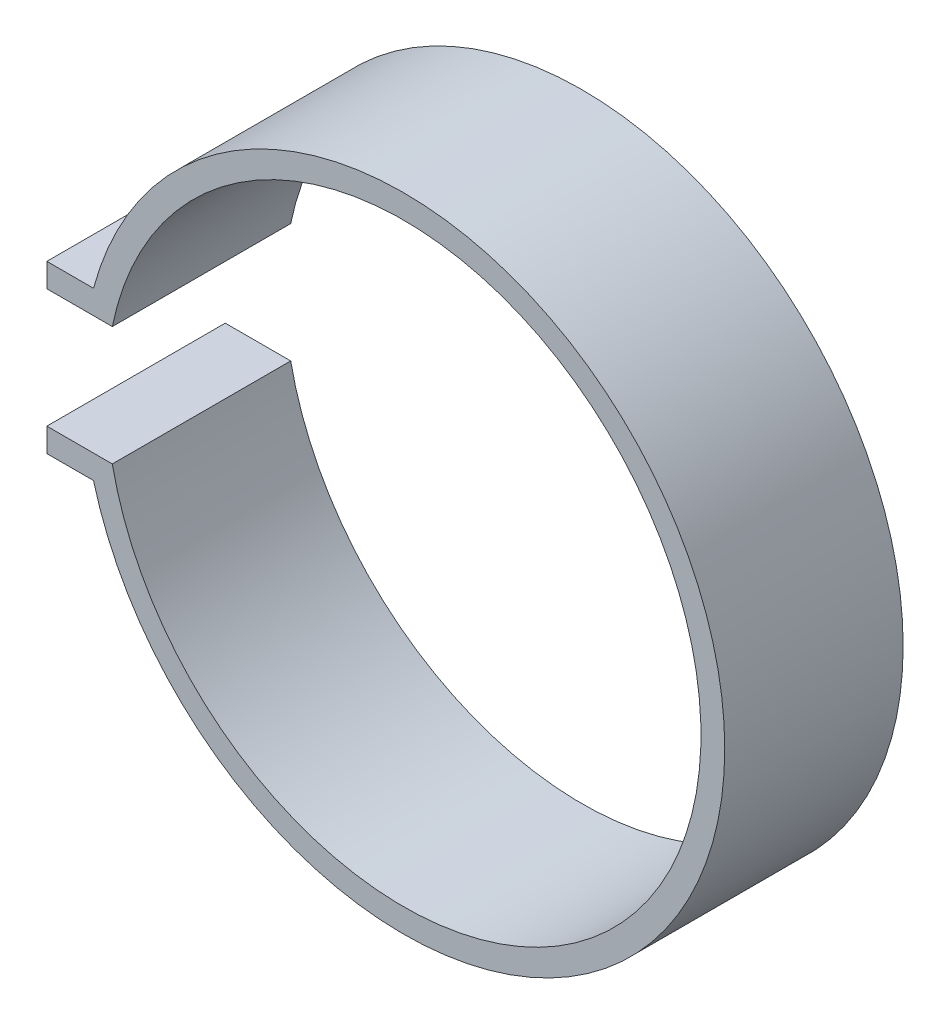
SolidWorks part; units mm, degrees
ref_plane "Front Plane" through (0, 0, 0) normal (0, 0, 1) x (1, 0, 0)
ref_plane "Top Plane" through (0, 0, 0) normal (0, 1, 0) x (1, 0, 0)
ref_plane "Right Plane" through (0, 0, 0) normal (1, 0, 0) x (0, 0, -1)
sketch "Sketch1" plane through (0, 0, 0) normal (0, 0, 1) x (1, 0, 0)
  line L0 (0, 0) -> (50507.6935, 0) construction
  line L1 (0, 0) -> (0, 50507.6935) construction
  line L2 (-60, 10) -> (-48.9898, 10)
  line L3 (-60, -10) -> (-48.9898, -10)
  arc A0 (-48.9898, -10) -> (-48.9898, 10) centre (0, 0) ccw
  dimension "D1" = 50
  dimension "D2" = 60
  dimension "D3" = 60
  dimension "D4" = 20
extrude "Extrude-Thin1" add sketch "Sketch1" along normal blind 30 thin thin type one direction wall 4
